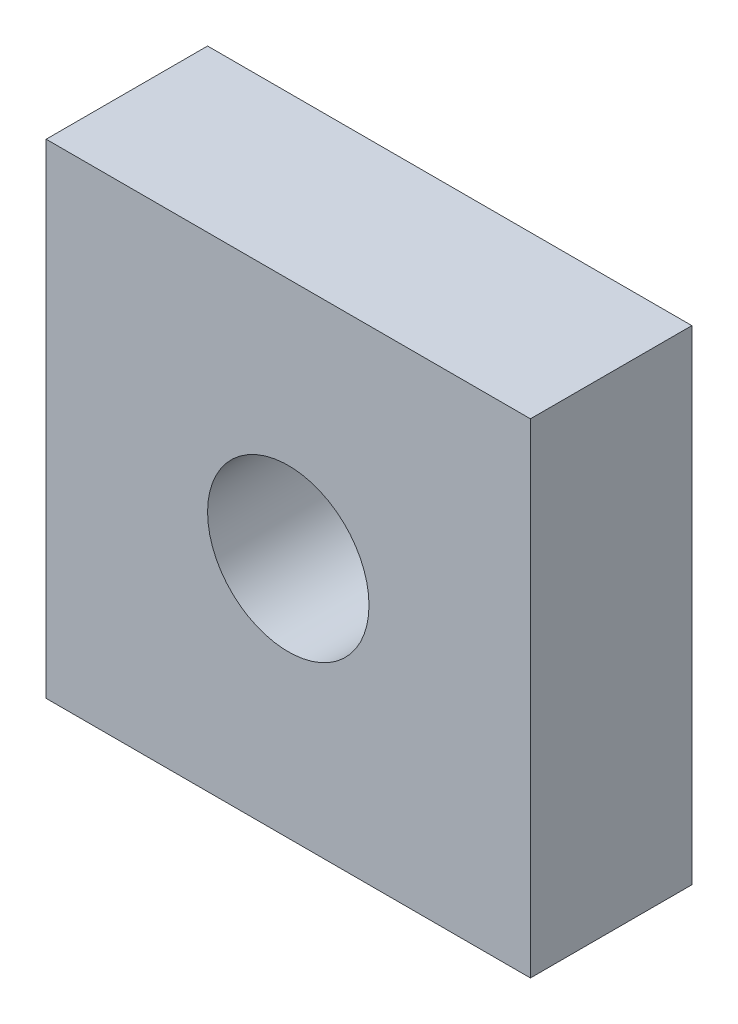
SolidWorks part; units mm, degrees
ref_plane "Front Plane" through (0, 0, 0) normal (0, 0, 1) x (1, 0, 0)
ref_plane "Top Plane" through (0, 0, 0) normal (0, 1, 0) x (1, 0, 0)
ref_plane "Right Plane" through (0, 0, 0) normal (1, 0, 0) x (0, 0, -1)
sketch "Sketch1" plane through (0, 0, 0) normal (0, 0, 1) x (1, 0, 0)
  line L1 (0, 0) -> (6, 0)
  line L2 (0, 0) -> (0, 6)
  line L3 (0, 6) -> (6, 6)
  line L4 (6, 0) -> (6, 6)
  dimension "D1" = 6
  dimension "D2" = 6
extrude "Boss-Extrude1" add sketch "Sketch1" along normal blind 2
sketch "Sketch2" plane through (0, 0, 0) normal (0, 0, -1) x (-1, 0, 0)
  line L0 (-3, 6) -> (-3, 0) construction
  line L1 (-6, 6) -> (0, 6) construction
  line L2 (0, 0) -> (-6, 0) construction
  circle A0 centre (-3, 3) radius 1
extrude "Cut-Extrude1" cut sketch "Sketch2" against normal through all
